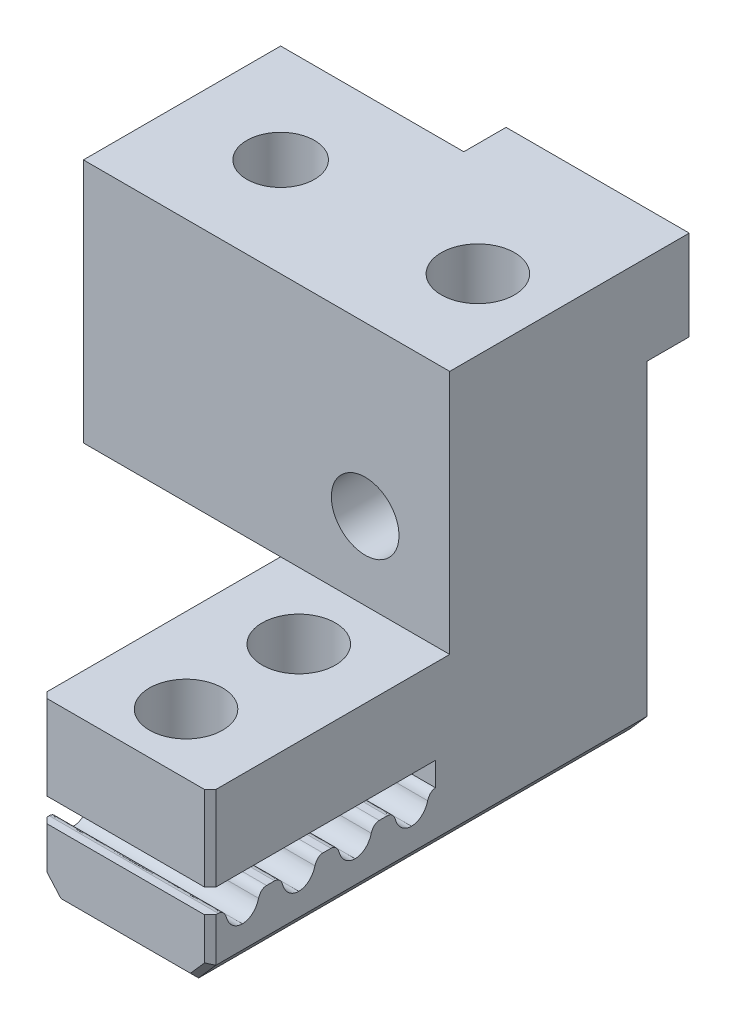
SolidWorks part; units mm, degrees
ref_plane "Front Plane" through (0, 0, 0) normal (0, 0, 1) x (1, 0, 0)
ref_plane "Top Plane" through (0, 0, 0) normal (0, 1, 0) x (1, 0, 0)
ref_plane "Right Plane" through (0, 0, 0) normal (1, 0, 0) x (0, 0, -1)
sketch "Sketch1" plane through (0, 0, 0) normal (0, 0, 1) x (1, 0, 0)
  line L0 (3, 3.05) -> (3, -2.2538)
  line L1 (-3, 3.05) -> (-3, -2.2538)
  line L7 (-3, 3.05) -> (3, 3.05)
  line L13 (-3, -2.2538) -> (-2.3882, -2.95)
  line L14 (3, -2.2538) -> (2.3882, -2.95)
  line L16 (-2.3882, -2.95) -> (2.3882, -2.95)
extrude "Boss-Extrude1" add sketch "Sketch1" along normal blind 13
sketch "Sketch6" plane through (0, 3.05, 0) normal (0, 1, 0) x (1, 0, 0)
  line L0 (-3, -5) -> (-3, 0)
  line L1 (-3, 0) -> (3, 0)
  line L3 (-3, -5) -> (3, -5)
  line L6 (3, -5) -> (3, 0)
  line L7 (3, 0) -> (-3, 0) construction
extrude "Boss-Extrude4" add sketch "Sketch6" along normal blind 5.6
sketch "Sketch16" plane through (0, 3.05, 0) normal (0, 1, 0) x (1, 0, 0)
  line L4 (3, -5) -> (-3, -5)
  line L5 (-3, -5) -> (-3, -13)
  line L6 (-3, -13) -> (3, -13)
  line L7 (3, -13) -> (3, -5)
  line L8 (3, -5) -> (-3, -5)
  line L9 (-3, -5) -> (-3, -13)
  line L10 (-3, -13) -> (3, -13)
  line L11 (3, -13) -> (3, -5)
  dimension "D1" = 0
extrude "Boss-Extrude5" add sketch "Sketch16" along normal blind 0.1
sketch "Sketch18" plane through (0, 0, 0) normal (1, 0, 0) x (0, 0, -1)
  line L0 (-8.8572, -0.0702) -> (-12.8572, -0.0702)
  line L2 (-12.8572, -0.7) -> (-12.7144, -0.7)
  line L3 (-11, -0.7) -> (-10.8572, -0.7)
  line L4 (-10.8572, -0.7) -> (-10.7144, -0.7)
  line L5 (-9, -0.7) -> (-8.8572, -0.7)
  line L6 (-8.8572, -0.7) -> (-8.7144, -0.7)
  line L7 (-7, -0.7) -> (-6.8572, -0.7)
  line L8 (-6.8572, -0.7) -> (-6.7144, -0.7)
  line L9 (-5, -0.0702) -> (-5, -0.7)
  line L11 (-5, -0.0702) -> (-8.8572, -0.0702)
  line L12 (-13, -2.95) -> (0, -2.95) construction
  line L13 (-5.8572, -1.45) -> (-5, -1.45) construction
  line L14 (-5, -1.45) -> (-11.8572, -1.45) construction
  line L15 (-5, 3.15) -> (-5, -1.45) construction
  line L16 (-5, -0.7) -> (-5, -1.45) construction
  line L17 (-12.8572, -0.0702) -> (-13, -0.0702)
  line L20 (-13, -0.0702) -> (-13, -0.7)
  line L22 (-12.8572, -0.7) -> (-13, -0.7)
  spline S0 degree 2 poles (-12.7144, -0.7) (-12.5198, -0.7) (-12.43, -0.9509) knots 0.103448 0.103448 0.103448 0.137931 0.137931 0.137931
  spline S1 degree 3 poles (-12.43, -0.9509) (-12.3594, -1.2388) (-12.13, -1.45) (-11.8572, -1.45) knots 0.137931 0.137931 0.137931 0.137931 0.172414 0.172414 0.172414 0.172414
  spline S2 degree 3 poles (-11.8572, -1.45) (-11.5844, -1.45) (-11.355, -1.2388) (-11.2844, -0.9509) knots 0.172414 0.172414 0.172414 0.172414 0.206897 0.206897 0.206897 0.206897
  spline S3 degree 2 poles (-11.2844, -0.9509) (-11.1946, -0.7) (-11, -0.7) knots 0.206897 0.206897 0.206897 0.241379 0.241379 0.241379
  spline S4 degree 2 poles (-10.7144, -0.7) (-10.5198, -0.7) (-10.43, -0.9509) knots 0.310345 0.310345 0.310345 0.344828 0.344828 0.344828
  spline S5 degree 3 poles (-10.43, -0.9509) (-10.3594, -1.2388) (-10.13, -1.45) (-9.8572, -1.45) knots 0.344828 0.344828 0.344828 0.344828 0.37931 0.37931 0.37931 0.37931
  spline S6 degree 3 poles (-9.8572, -1.45) (-9.5844, -1.45) (-9.355, -1.2388) (-9.2844, -0.9509) knots 0.37931 0.37931 0.37931 0.37931 0.413793 0.413793 0.413793 0.413793
  spline S7 degree 2 poles (-9.2844, -0.9509) (-9.1946, -0.7) (-9, -0.7) knots 0.413793 0.413793 0.413793 0.448276 0.448276 0.448276
  spline S8 degree 2 poles (-8.7144, -0.7) (-8.5198, -0.7) (-8.43, -0.9509) knots 0.517241 0.517241 0.517241 0.551724 0.551724 0.551724
  spline S9 degree 3 poles (-8.43, -0.9509) (-8.3594, -1.2388) (-8.13, -1.45) (-7.8572, -1.45) knots 0.551724 0.551724 0.551724 0.551724 0.586207 0.586207 0.586207 0.586207
  spline S10 degree 3 poles (-7.8572, -1.45) (-7.5844, -1.45) (-7.355, -1.2388) (-7.2844, -0.9509) knots 0.586207 0.586207 0.586207 0.586207 0.62069 0.62069 0.62069 0.62069
  spline S11 degree 2 poles (-7.2844, -0.9509) (-7.1946, -0.7) (-7, -0.7) knots 0.62069 0.62069 0.62069 0.655172 0.655172 0.655172
  spline S12 degree 2 poles (-6.7144, -0.7) (-6.5198, -0.7) (-6.43, -0.9509) knots 0.724138 0.724138 0.724138 0.758621 0.758621 0.758621
  spline S13 degree 3 poles (-6.43, -0.9509) (-6.3594, -1.2388) (-6.13, -1.45) (-5.8572, -1.45) knots 0.758621 0.758621 0.758621 0.758621 0.793103 0.793103 0.793103 0.793103
  spline S14 degree 3 poles (-5.8572, -1.45) (-5.5844, -1.45) (-5.355, -1.2388) (-5.2844, -0.9509) knots 0.793103 0.793103 0.793103 0.793103 0.827586 0.827586 0.827586 0.827586
  spline S15 degree 2 poles (-5.2844, -0.9509) (-5.1946, -0.7) (-5, -0.7) knots 0.827586 0.827586 0.827586 0.862069 0.862069 0.862069
  dimension "D1" = 1.5
  dimension "D2" = 1.3798
extrude "Cut-Extrude6" cut sketch "Sketch18" against normal blind 3.6 and the other way blind 4
sketch "Sketch15" plane through (0, 8.65, 0) normal (0, 1, 0) x (1, 0, 0)
  line L0 (0, -13) -> (0, -5) construction
  line L1 (-3, -13) -> (3, -13) construction
  line L2 (-3, -5) -> (3, -5) construction
  line L3 (2.008, -10.7144) -> (2.008, -11) construction
  line L4 (3, -10.7144) -> (-3, -10.7144) construction
  line L5 (3, -11) -> (-3, -11) construction
  line L6 (2.008, -10.8572) -> (0, -10.8572) construction
  line L7 (1.0382, -6.7144) -> (1.0382, -7) construction
  line L8 (3, -6.7144) -> (-3, -6.7144) construction
  line L9 (3, -7) -> (-3, -7) construction
  line L10 (1.0382, -6.8572) -> (0, -6.8572) construction
  circle A0 centre (0, -6.8572) radius 1.5 construction
  circle A1 centre (0, -10.8572) radius 1.5 construction
  circle A2 centre (0, -10.8572) radius 1.3
  circle A4 centre (0, -6.8572) radius 1.3
  dimension "D1" = 2.6
  dimension "D2" = 2.6
extrude "Cut-Extrude7" cut sketch "Sketch15" against normal up to surface (8.7202 mm away) up to face at (0, -0.0702, 9)
sketch "Sketch19" plane through (0, -0.0702, 0) normal (0, -1, 0) x (1, 0, 0)
  line L4 (-3, 13) -> (-3, 5)
  line L5 (-3, 5) -> (3, 5)
  line L6 (3, 5) -> (3, 13)
  line L7 (3, 13) -> (-3, 13)
  line L8 (-3, 13) -> (-3, 5)
  line L9 (-3, 5) -> (3, 5)
  line L10 (3, 5) -> (3, 13)
  line L11 (3, 13) -> (-3, 13)
  circle A0 centre (0, 10.8572) radius 1.3 construction
  circle A1 centre (0, 6.8572) radius 1.3 construction
  circle A2 centre (0, 10.8572) radius 1.3
  circle A3 centre (0, 6.8572) radius 1.3
  dimension "D1" = 0
extrude "Cut-Extrude8" cut sketch "Sketch19" against normal blind 0.2202
sketch "Sketch12" plane through (0, 0, 5) normal (0, 0, 1) x (1, 0, 0)
  circle A0 centre (0, 5.85) radius 1.5 construction
  circle A1 centre (0, 5.85) radius 1.2
extrude "Cut-Extrude5" cut sketch "Sketch12" against normal blind 6
chamfer "Chamfer1" distance 0.2 angle 45 7 edges at (-3, 1.65, 13) (-3, -1.4769, 13) (-2.6941, -2.6019, 13) (0, -2.95, 13) (2.6941, -2.6019, 13) (3, -1.4769, 13) (3, 1.65, 13)
sketch "Sketch21" plane through (0, 0, 0) normal (0, 0, -1) x (-1, 0, 0)
  line L10 (-2.3882, -2.95) -> (2.3882, -2.95)
  line L11 (2.3882, -2.95) -> (3, -2.2538)
  line L12 (3, -2.2538) -> (3, 8.65)
  line L13 (3, 8.65) -> (-3, 8.65)
  line L14 (-3, 8.65) -> (-3, -2.2538)
  line L15 (-3, -2.2538) -> (-2.3882, -2.95)
  line L19 (-2.3882, -2.95) -> (2.3882, -2.95)
  line L20 (2.3882, -2.95) -> (3, -2.2538)
  line L21 (3, -2.2538) -> (3, 8.65)
  line L22 (3, 8.65) -> (-3, 8.65)
  line L23 (-3, 8.65) -> (-3, -2.2538)
  line L24 (-3, -2.2538) -> (-2.3882, -2.95)
  circle A0 centre (0, 5.85) radius 1.2 construction
  circle A1 centre (0, 5.85) radius 1.2
  dimension "D1" = 0
extrude "Boss-Extrude6" add sketch "Sketch21" along normal blind 2.5
sketch "Sketch24" plane through (0, 0, 5) normal (0, 0, 1) x (1, 0, 0)
  line L4 (-3, 8.65) -> (-3, 3.15)
  line L5 (-3, 3.15) -> (3, 3.15)
  line L6 (3, 3.15) -> (3, 8.65)
  line L7 (3, 8.65) -> (-3, 8.65)
  line L8 (-3, 8.65) -> (-3, 3.15)
  line L9 (-3, 3.15) -> (3, 3.15)
  line L10 (3, 3.15) -> (3, 8.65)
  line L11 (3, 8.65) -> (-3, 8.65)
  dimension "D1" = 0
extrude "Cut-Extrude10" cut sketch "Sketch24" against normal blind 8.5
sketch "Sketch25" plane through (0, 3.15, 0) normal (0, 1, 0) x (1, 0, 0)
  line L0 (3, -12.8) -> (3, 2.5) construction
  line L2 (-3, 2.5) -> (3, 2.5)
  line L3 (-3, 2.5) -> (-3, -4.5)
  line L4 (-3, -4.5) -> (3, -4.5)
  line L5 (3, 2.5) -> (3, -4.5)
  dimension "D1" = 7
extrude "Boss-Extrude8" add sketch "Sketch25" along normal blind 12.9
sketch "Sketch26" plane through (0, 0, -2.5) normal (0, 0, -1) x (-1, 0, 0)
  line L0 (3, -2.2538) -> (3, 16.05) construction
  line L1 (-3, 16.05) -> (3, 16.05)
  line L2 (-3, 16.05) -> (-3, 8.66)
  line L3 (-3, 8.66) -> (3, 8.66)
  line L4 (3, 16.05) -> (3, 8.66)
extrude "Boss-Extrude9" add sketch "Sketch26" along normal blind 3
sketch "Sketch30" plane through (0, 0, -2.5) normal (0, 0, -1) x (-1, 0, 0)
  circle A2 centre (0, 5.9) radius 1.2
extrude "Cut-Extrude13" cut sketch "Sketch30" against normal blind 8
sketch "Sketch31" plane through (3, 0, 0) normal (1, 0, 0) x (0, 0, -1)
  line L1 (-4.5, 12.15) -> (2.5, 12.15)
  line L2 (-4.5, 12.15) -> (-4.5, 3.15)
  line L3 (-4.5, 3.15) -> (2.5, 3.15)
  line L4 (2.5, 12.15) -> (2.5, 3.15)
  line L5 (-12.8, 3.15) -> (-4.5, 3.15) construction
extrude "Boss-Extrude11" add sketch "Sketch31" along normal blind 1
sketch "Sketch32" plane through (-3, 0, 0) normal (-1, 0, 0) x (0, 0, 1)
  line L0 (-2.5, -2.2538) -> (-2.5, 8.66) construction
  line L1 (4.5, 12.15) -> (-2.5, 12.15)
  line L2 (4.5, 12.15) -> (4.5, 3.15)
  line L3 (4.5, 3.15) -> (-2.5, 3.15)
  line L4 (-2.5, 12.15) -> (-2.5, 3.15)
  line L6 (4.5, 3.15) -> (12.8, 3.15) construction
extrude "Boss-Extrude12" add sketch "Sketch32" along normal blind 1
sketch "Sketch33" plane through (3, 0, 0) normal (1, 0, 0) x (0, 0, -1)
  line L6 (2.5, 12.15) -> (2.5, 8.66)
  line L7 (2.5, 8.66) -> (5.5, 8.66)
  line L8 (5.5, 8.66) -> (5.5, 16.05)
  line L9 (5.5, 16.05) -> (-4.5, 16.05)
  line L10 (-4.5, 16.05) -> (-4.5, 12.15)
  line L11 (-4.5, 12.15) -> (2.5, 12.15)
  line L12 (2.5, 12.15) -> (2.5, 8.66)
  line L13 (2.5, 8.66) -> (5.5, 8.66)
  line L14 (5.5, 8.66) -> (5.5, 16.05)
  line L15 (5.5, 16.05) -> (-4.5, 16.05)
  line L16 (-4.5, 16.05) -> (-4.5, 12.15)
  line L17 (-4.5, 12.15) -> (2.5, 12.15)
  dimension "D1" = 0
extrude "Boss-Extrude13" add sketch "Sketch33" along normal up to surface (1 mm away) up to face at (4, 7.65, 1)
sketch "Sketch34" plane through (-3, 0, 0) normal (-1, 0, 0) x (0, 0, 1)
  line L6 (-2.5, 12.15) -> (4.5, 12.15)
  line L7 (4.5, 12.15) -> (4.5, 16.05)
  line L8 (4.5, 16.05) -> (-5.5, 16.05)
  line L9 (-5.5, 16.05) -> (-5.5, 8.66)
  line L10 (-5.5, 8.66) -> (-2.5, 8.66)
  line L11 (-2.5, 8.66) -> (-2.5, 12.15)
  line L12 (-2.5, 12.15) -> (4.5, 12.15)
  line L13 (4.5, 12.15) -> (4.5, 16.05)
  line L14 (4.5, 16.05) -> (-5.5, 16.05)
  line L15 (-5.5, 16.05) -> (-5.5, 8.66)
  line L16 (-5.5, 8.66) -> (-2.5, 8.66)
  line L17 (-2.5, 8.66) -> (-2.5, 12.15)
  dimension "D1" = 0
extrude "Boss-Extrude14" add sketch "Sketch34" along normal up to surface (1 mm away) up to face at (-4, 7.65, 1)
sketch "Sketch35" plane through (-4, 0, 0) normal (-1, 0, 0) x (0, 0, 1)
  line L0 (4.5, 3.15) -> (4.5, 16.05) construction
  line L1 (-5.5, 16.05) -> (4.5, 16.05)
  line L2 (-5.5, 16.05) -> (-5.5, 11.85)
  line L3 (-5.5, 11.85) -> (4.5, 11.85)
  line L4 (4.5, 16.05) -> (4.5, 11.85)
  dimension "D1" = 4.2
extrude "Cut-Extrude14" cut sketch "Sketch35" against normal blind 10
sketch "Sketch36" plane through (-4, 0, 0) normal (-1, 0, 0) x (0, 0, 1)
  line L6 (4.5, 3.15) -> (4.5, 11.85)
  line L7 (4.5, 11.85) -> (-5.5, 11.85)
  line L8 (-5.5, 11.85) -> (-5.5, 8.66)
  line L9 (-5.5, 8.66) -> (-2.5, 8.66)
  line L10 (-2.5, 8.66) -> (-2.5, 3.15)
  line L11 (-2.5, 3.15) -> (4.5, 3.15)
  line L12 (4.5, 3.15) -> (4.5, 11.85)
  line L13 (4.5, 11.85) -> (-5.5, 11.85)
  line L14 (-5.5, 11.85) -> (-5.5, 8.66)
  line L15 (-5.5, 8.66) -> (-2.5, 8.66)
  line L16 (-2.5, 8.66) -> (-2.5, 3.15)
  line L17 (-2.5, 3.15) -> (4.5, 3.15)
  dimension "D1" = 0
extrude "Boss-Extrude15" add sketch "Sketch36" along normal blind 6
sketch "Sketch38" plane through (0, 11.85, 0) normal (0, 1, 0) x (1, 0, 0)
  line L0 (-3, 5.5) -> (-3, -4.5) construction
  line L1 (4, 5.5) -> (-10, 5.5) construction
  line L2 (4, -4.5) -> (-10, -4.5) construction
  line L3 (-3, 2.5) -> (-10, -4.5) construction
  line L5 (0, -13) -> (0, 5.5) construction
  line L6 (-2.8, -13) -> (2.8, -13) construction
  line L7 (4, 2.5) -> (-10, 2.5) construction
  line L8 (4, 2.5) -> (-3, -4.5) construction
  line L9 (-3, 2.5) -> (4, -4.5) construction
  circle A0 centre (-6.5, -1) radius 1.3 construction
  circle A1 centre (0.5, -1) radius 1.3
  dimension "D1" = 2.6
extrude "Cut-Extrude15" cut sketch "Sketch38" against normal blind 4
sketch "Sketch39" plane through (0, 11.85, 0) normal (0, 1, 0) x (1, 0, 0)
  circle A0 centre (-6.5, -1) radius 1.2
extrude "Cut-Extrude16" cut sketch "Sketch39" against normal blind 10
sketch "Sketch40" plane through (0, 11.85, 0) normal (0, 1, 0) x (1, 0, 0)
  line L1 (4, 4) -> (-10, 4)
  line L2 (-10, 4) -> (-10, 5.5)
  line L4 (-10, 5.5) -> (4, 5.5)
  line L5 (4, 5.5) -> (4, 4)
extrude "Cut-Extrude17" cut sketch "Sketch40" against normal blind 10
sketch "Sketch41" plane through (0, 0, -4) normal (0, 0, -1) x (-1, 0, 0)
  line L0 (-4, 8.66) -> (10, 8.66) construction
  line L1 (10, 11.85) -> (3.5, 11.85)
  line L2 (10, 11.85) -> (10, 8.66)
  line L3 (10, 8.66) -> (3.5, 8.66)
  line L4 (3.5, 11.85) -> (3.5, 8.66)
extrude "Cut-Extrude18" cut sketch "Sketch41" against normal up to surface (1.5 mm away) up to face at (-1.2, 5.9, -2.5)
sketch "Croquis3" plane through (4, 0, 0) normal (1, 0, 0) x (0, 0, -1)
  line L1 (-4.5, 11.85) -> (4, 11.85)
  line L2 (-4.5, 11.85) -> (-4.5, 3.1233)
  line L3 (-4.5, 3.1233) -> (4, 3.1233)
  line L4 (4, 11.85) -> (4, 3.1233)
extrude "Cortar-Extruir3" cut sketch "Croquis3" against normal up to surface (1 mm away) up to face at (3, -0.5166, 8.4383)
